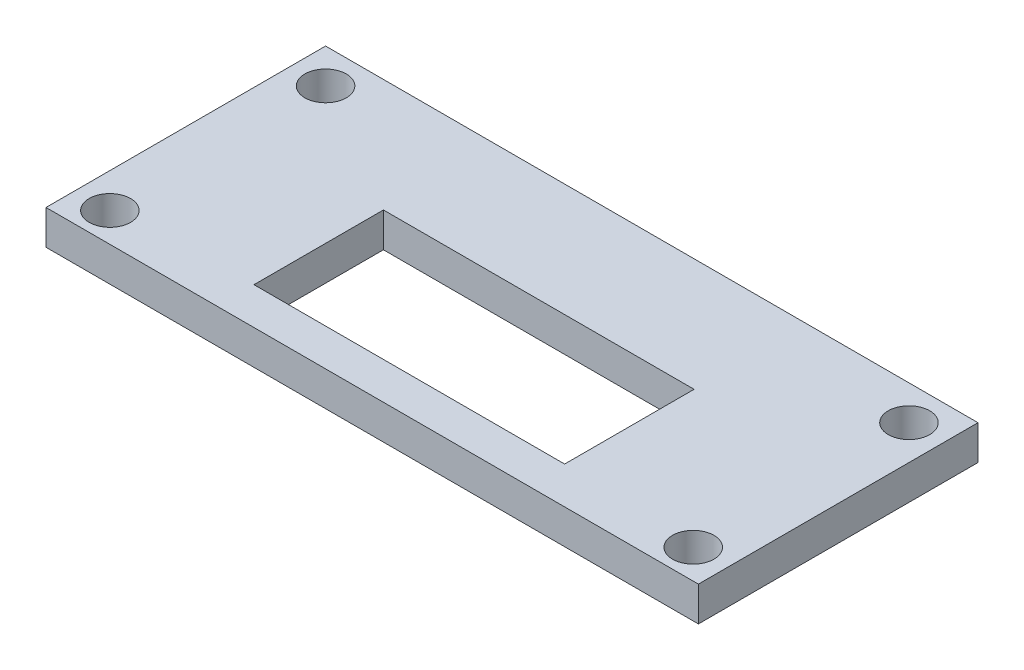
SolidWorks part; units mm, degrees
ref_plane "Front Plane" through (0, 0, 0) normal (0, 0, 1) x (1, 0, 0)
ref_plane "Top Plane" through (0, 0, 0) normal (0, 1, 0) x (1, 0, 0)
ref_plane "Right Plane" through (0, 0, 0) normal (1, 0, 0) x (0, 0, -1)
ref_plane "PZ15" through (0, 15, 0) normal (0, 1, 0) x (1, 0, 0)
sketch "Sketch1" plane through (0, 15, 0) normal (0, 1, 0) x (1, 0, 0)
  line L0 (-18.9, 29.3) -> (18.9, 29.3)
  line L1 (18.9, 29.3) -> (18.9, 45.5)
  line L2 (18.9, 45.5) -> (-18.9, 45.5)
  line L3 (-18.9, 45.5) -> (-18.9, 29.3)
extrude "Retainer Plate" add sketch "Sketch1" along normal blind 2
ref_plane "PZ14" through (0, 14, 0) normal (0, 1, 0) x (1, 0, 0)
sketch "Sketch2" plane through (0, 14, 0) normal (0, 1, 0) x (1, 0, 0)
  line L0 (-9, 31.45) -> (9, 31.45)
  line L1 (9, 31.45) -> (9, 38.95)
  line L2 (9, 38.95) -> (-9, 38.95)
  line L3 (-9, 38.95) -> (-9, 31.45)
extrude "Ribbon Slot" cut sketch "Sketch2" along normal blind 4
sketch "Sketch3" plane through (0, 14, 0) normal (0, 1, 0) x (1, 0, 0)
  circle A0 centre (-16.9, 31) radius 1.2
  circle A1 centre (-16.9, 43.5) radius 1.2
  circle A2 centre (16.9, 31) radius 1.2
  circle A3 centre (16.9, 43.5) radius 1.2
extrude "M2 Clearance Holes" cut sketch "Sketch3" along normal blind 4
equation "\"BOARD_REAR\" = 86.0"
equation "\"BOARD_FRONT\" = 41.0"
equation "\"BOARD_END\" = 22.0"
equation "\"BOARD_ANGLED\" = 30.0"
equation "\"BOARD_DEPTH\" = 41.8431"
equation "\"PCB_T\" = 1.6"
equation "\"ABOVE_PCB\" = 14.0"
equation "\"BELOW_PCB\" = 6.0"
equation "\"MID_PARTS_H\" = 9.0"
equation "\"BOARD_HOLE_PILOT\" = 1.6"
equation "\"J2_X\" = 19.0"
equation "\"DUPONT_DROP\" = 14.0"
equation "\"BEND_R\" = 5.0"
equation "\"BOARD_GAP\" = 3.0"
equation "\"TOF_FOV\" = 25.0"
equation "\"TOF_MARGIN_DEG\" = 5.0"
equation "\"TOF_WIN_MARGIN\" = 1.0"
equation "\"TOF_Z\" = 9.0"
equation "\"TOF_SIDE_BEARING\" = 90.0"
equation "\"TOF_CONE_LEN\" = 70.0"
equation "\"CAM_W\" = 29.2"
equation "\"CAM_H\" = 28.2"
equation "\"CAM_D\" = 12.35"
equation "\"CAM_FRONT_Y\" = 43.0"
equation "\"CAM_BOTTOM_Z\" = 17.0"
equation "\"CAM_LENS_UP\" = 11.6"
equation "\"CAM_LENS_OPEN\" = 9.6"
equation "\"CAM_HFOV\" = 53.5"
equation "\"CAM_VFOV\" = 41.41"
equation "\"CAM_FOV_MARGIN\" = 3.0"
equation "\"CAM_FIT\" = 0.3"
equation "\"RIBBON_W\" = 16.0"
equation "\"RIBBON_T\" = 0.3"
equation "\"RIBBON_LEN\" = 150.0"
equation "\"RIBBON_EXIT_Y\" = 35.0"
equation "\"WALL\" = 2.4"
equation "\"HEAD_X\" = 48.4"
equation "\"HEAD_REAR_Y\" = -11.9"
equation "\"CAM_FOAM\" = 2.8"
equation "\"HEAD_FRONT_Y\" = 48.2"
equation "\"HEAD_TOP_Z\" = 50.6"
equation "\"HEAD_BOT_Z\" = -28.4"
equation "\"HEAD_SPLIT_Z\" = -4.0"
equation "\"SKIRT_T\" = 1.2"
equation "\"SKIRT_H\" = 3.0"
equation "\"SKIRT_FIT\" = 0.3"
equation "\"VISOR\" = 7.8"
equation "\"VISOR_Z\" = 40.0"
equation "\"ROOF_SLOPE_Y\" = 40.0"
equation "\"ROOF_CHAMFER\" = 10.0"
equation "\"REAR_CHAMFER\" = 10.0"
equation "\"CORNER_CHAMFER\" = 6.0"
equation "\"LOWER_SIDE_FACET\" = 6.0"
equation "\"LIGHTBAR_DEPTH\" = 1.0"
equation "\"HOOD_Z\" = 14.0"
equation "\"HOOD_L\" = 6.0"
equation "\"SIDE_HOOD_L\" = 4.0"
equation "\"INSERT_M3_D\" = 4.0"
equation "\"INSERT_M3_L\" = 6.0"
equation "\"M3_CLEAR\" = 3.4"
equation "\"M2_PILOT\" = 1.6"
equation "\"M25_PILOT\" = 2.2"
equation "\"BOX_X\" = 72.4"
equation "\"BOX_FRONT_Y\" = -11.9"
equation "\"BOX_REAR_Y\" = -124.4"
equation "\"BOX_BOT_Z\" = -28.4"
equation "\"BOX_TOP_Z\" = 26.0"
equation "\"LID_T\" = 2.4"
equation "\"LID_SKIRT\" = 1.6"
equation "\"LID_TONGUE_H\" = 3.0"
equation "\"LID_FIT\" = 0.3"
equation "\"PI_STANDOFF\" = 8.0"
equation "\"BOX_REAR_CHAMFER\" = 8.0"
equation "\"BOX_REAR_FACET\" = 4.0"
equation "\"VENT_UPSTAND\" = 3.0"
equation "\"TUBE_D\" = 22.2"
equation "\"TUBE_LINER\" = 1.0"
equation "\"MOUNT_Y\" = -70.0"
equation "\"RAIL_W\" = 30.0"
equation "\"RAIL_W2\" = 38.0"
equation "\"RAIL_H\" = 6.0"
equation "\"SLIDE\" = 0.3"
equation "\"STOP_T\" = 6.0"
equation "\"CLAMP_W\" = 40.0"
equation "\"CLAMP_HALF\" = 20.0"
equation "\"CLAMP_DROP\" = 12.0"
equation "\"CAP_T\" = 12.0"
equation "\"CLAMP_BOLT_OFF\" = 16.6"
equation "\"M5_INSERT_D\" = 6.4"
equation "\"M5_CLEAR\" = 5.5"
equation "\"LOCK_D\" = 3.3"
equation "\"POD_TILT_DEG\" = 0.0"
equation "\"PRINT_LIMIT\" = 180.0"
equation "\"PI5_L\" = 85.0"
equation "\"PI5_W\" = 56.0"
equation "\"PI5_T\" = 1.6"
equation "\"PI5_USBC_BX\" = 11.2"
equation "\"PI5_ETH_BY\" = 10.2"
equation "\"PI5_PORT_OVERHANG\" = 3.0"
equation "\"PI5_FPC_H\" = 5.0"
equation "\"PI5_FPC_USE\" = 0.0"
equation "\"PI5_PIN1_BX\" = 8.37"
equation "\"HEADER_BASE_H\" = 2.5"
equation "\"DUPONT_L\" = 14.0"
equation "\"PI5_UNDERSIDE\" = 1.5"
equation "\"COOLER_H\" = 15.0"
equation "\"HAT_W\" = 65.0"
equation "\"HAT_D\" = 56.5"
equation "\"HAT_T\" = 1.6"
equation "\"HAT_SPACER\" = 16.0"
equation "\"HAILO_H\" = 10.0"
equation "\"STACK_PINS_H\" = 6.0"
equation "\"DUPONT_SEAT\" = 0.5"
equation "\"PCIE_FFC_LOOP\" = 6.0"
equation "\"HAILO_AIR_GAP_MIN\" = 8.0"
equation "\"M25_CLEAR\" = 2.7"
equation "\"PI_X0\" = -55.0"
equation "\"PI_Y1\" = -36.5"
equation "\"PI_Y0\" = -92.5"
equation "\"BOX_LEN\" = 112.5"
equation "\"COVER_T\" = 3.0"
equation "\"COVER_TOP_Z\" = 6.5"
equation "\"SIDE_LEDGE_Z\" = -2.5"
equation "\"UPPER_LEDGE_Z\" = 15.5"
equation "\"REAR_LEDGE_Z\" = 8.0"
equation "\"LEDGE_L\" = 4.0"
equation "\"RIBBON_W_PI\" = 11.5"
equation "\"RIBBON_RUN_Z\" = 12.0"
equation "\"RIBBON_SPEC_LEN\" = 200.0"
